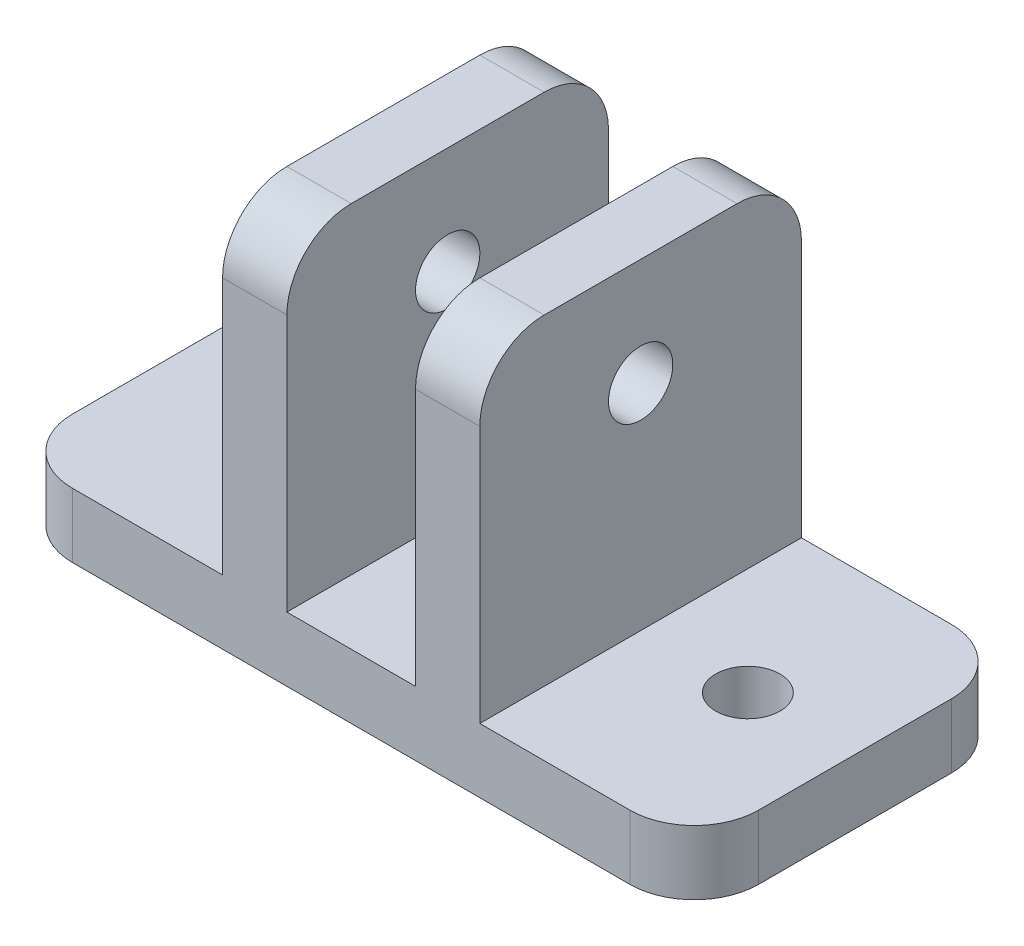
SolidWorks part; units mm, degrees
ref_plane "Alzado" through (0, 0, 0) normal (0, 0, 1) x (1, 0, 0)
ref_plane "Planta" through (0, 0, 0) normal (0, 1, 0) x (1, 0, 0)
ref_plane "Vista lateral" through (0, 0, 0) normal (1, 0, 0) x (0, 0, -1)
sketch "Croquis1" plane through (0, 0, 0) normal (0, 1, 0) x (1, 0, 0)
  line L1 (-19, 7.5) -> (19, 7.5)
  line L2 (-19, 7.5) -> (-19, -7.5)
  line L3 (-19, -7.5) -> (19, -7.5)
  line L4 (19, 7.5) -> (19, -7.5)
  line L5 (-19, 7.5) -> (19, -7.5) construction
  line L6 (-19, -7.5) -> (19, 7.5) construction
  point P0 (0, 0)
  dimension "D1" = 38
  dimension "D2" = 15
extrude "Saliente-Extruir1" add sketch "Croquis1" along normal blind 3
sketch "Croquis2" plane through (0, 3, 0) normal (0, 1, 0) x (1, 0, 0)
  line L0 (19, 7.5) -> (-19, 7.5) construction
  line L1 (-9, 7.5) -> (-6, 7.5)
  line L2 (-9, 7.5) -> (-9, -7.5)
  line L3 (-9, -7.5) -> (-6, -7.5)
  line L4 (-6, 7.5) -> (-6, -7.5)
  line L5 (-19, 7.5) -> (-19, -7.5) construction
  line L6 (0, 7.5) -> (3, 7.5)
  line L7 (0, 7.5) -> (0, -7.5)
  line L8 (0, -7.5) -> (3, -7.5)
  line L9 (3, 7.5) -> (3, -7.5)
  dimension "D1" = 10
  dimension "D2" = 6
  dimension "D3" = 3
  dimension "D4" = 3
extrude "Saliente-Extruir2" add sketch "Croquis2" along normal blind 15
sketch "Croquis3" plane through (0, 3, 0) normal (0, 1, 0) x (1, 0, 0)
  line L0 (19, 7.5) -> (3, 7.5) construction
  line L1 (13, 7.5) -> (19, 7.5)
  line L2 (13, 7.5) -> (13, -7.5)
  line L3 (13, -7.5) -> (19, -7.5)
  line L4 (19, 7.5) -> (19, -7.5)
  line L5 (3, -7.5) -> (3, 7.5) construction
  dimension "D1" = 10
extrude "Cortar-Extruir1" cut sketch "Croquis3" against normal blind 15
sketch "Croquis4" plane through (0, 3, 0) normal (0, 1, 0) x (1, 0, 0)
  line L0 (-19, 7.5) -> (-16, 7.5) construction
  line L1 (-9, 7.5) -> (-19, 7.5) construction
  line L2 (-16, 7.5) -> (-16, 4.5) construction
  line L3 (13, 4.5) -> (10, 4.5) construction
  line L4 (13, 7.5) -> (13, -7.5) construction
  line L5 (-16, -7.5) -> (-16, -4.5) construction
  line L6 (-19, -7.5) -> (-9, -7.5) construction
  line L7 (3, -7.5) -> (13, -7.5) construction
  line L8 (13, 7.5) -> (3, 7.5) construction
  line L9 (-19, 7.5) -> (-19, -7.5) construction
  line L10 (-19, 4.5) -> (-19, 7.5)
  line L11 (-19, 7.5) -> (-16, 7.5)
  line L12 (10, 7.5) -> (13, 7.5)
  line L13 (13, 7.5) -> (13, 4.5)
  line L14 (13, -4.5) -> (13, -7.5)
  line L15 (13, -7.5) -> (10, -7.5)
  line L16 (-16, -7.5) -> (-19, -7.5)
  line L17 (-19, -7.5) -> (-19, -4.5)
  arc A0 (13, -4.5) -> (10, -7.5) centre (10, -4.5) cw
  arc A1 (10, 7.5) -> (13, 4.5) centre (10, 4.5) cw
  arc A2 (-19, -4.5) -> (-16, -7.5) centre (-16, -4.5) ccw
  arc A3 (-19, 4.5) -> (-16, 7.5) centre (-16, 4.5) cw
  line M2 (-9, 7.5) -> (-19, 7.5)
  line M3 (-19, 7.5) -> (-19, -7.5)
  line M4 (-19, -7.5) -> (-9, -7.5)
extrude "Cortar-Extruir2" cut sketch "Croquis4" against normal blind 15 contours A3 M3 M2 | A2 M3 M4 | L14 A0 L15 | L12 A1 L13
sketch "Croquis5" plane through (-9, 0, 0) normal (-1, 0, 0) x (0, 0, 1)
  line L0 (-7.5, 18) -> (-7.5, 15) construction
  line L1 (-7.5, 18) -> (-7.5, 3) construction
  line L2 (-7.5, 15) -> (-4.5, 15) construction
  line L3 (7.5, 15) -> (4.5, 15) construction
  line L4 (7.5, 18) -> (7.5, 3) construction
  line L5 (-4.5, 18) -> (-7.5, 18)
  line L6 (-7.5, 18) -> (-7.5, 15)
  line L7 (4.5, 18) -> (7.5, 18)
  line L8 (7.5, 18) -> (7.5, 15)
  arc A0 (-7.5, 15) -> (-4.5, 18) centre (-4.5, 15) cw
  arc A1 (7.5, 15) -> (4.5, 18) centre (4.5, 15) ccw
extrude "Cortar-Extruir3" cut sketch "Croquis5" against normal blind 15
sketch "Croquis6" plane through (-9, 0, 0) normal (-1, 0, 0) x (0, 0, 1)
  line L0 (-4.5, 18) -> (4.5, 18) construction
  circle A0 centre (0, 13) radius 1.5
  dimension "D1" = 5
extrude "Cortar-Extruir4" cut sketch "Croquis6" against normal blind 15
sketch "Croquis7" plane through (0, 3, 0) normal (0, 1, 0) x (1, 0, 0)
  line L0 (-19, 4.5) -> (-19, -4.5) construction
  line L1 (13, 4.5) -> (13, -4.5) construction
  circle A0 centre (-14, 0) radius 1.5
  circle A1 centre (8, 0) radius 1.5
  dimension "D1" = 5
  dimension "D2" = 5
extrude "Cortar-Extruir5" cut sketch "Croquis7" against normal blind 15
